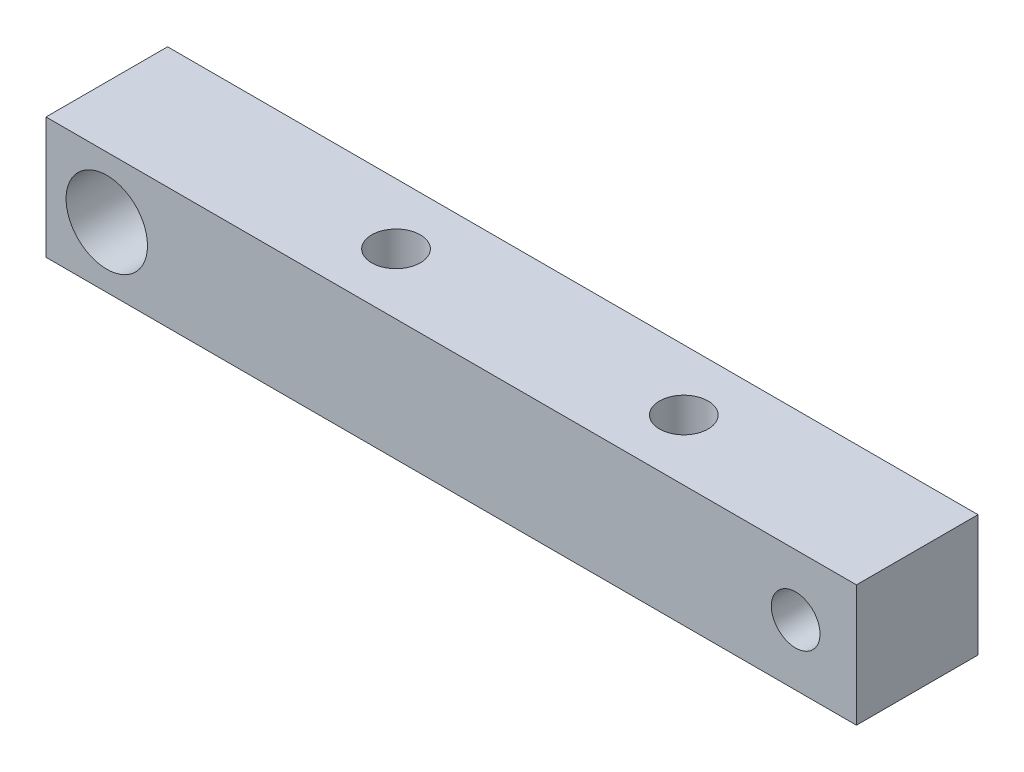
SolidWorks part; units mm, degrees
ref_plane "前基準面" through (0, 0, 0) normal (0, 0, 1) x (1, 0, 0)
ref_plane "上基準面" through (0, 0, 0) normal (0, 1, 0) x (1, 0, 0)
ref_plane "右基準面" through (0, 0, 0) normal (1, 0, 0) x (0, 0, -1)
sketch "草圖1" plane through (0, 0, 0) normal (0, 0, 1) x (1, 0, 0)
  line L1 (89.6066, 43.1835) -> (-10.3934, 43.1835)
  line L2 (89.6066, 43.1835) -> (89.6066, 28.1835)
  line L3 (89.6066, 28.1835) -> (-10.3934, 28.1835)
  line L4 (-10.3934, 43.1835) -> (-10.3934, 28.1835)
  circle A0 centre (82.1066, 35.6835) radius 3
  circle A1 centre (-2.8934, 35.6835) radius 5.0217
  dimension "D3" = 6
  dimension "D4" = 7.5
  dimension "D5" = 7.5
  dimension "D6" = 7.5
  dimension "D7" = 7.5
  dimension "D1" = 15
  dimension "D2" = 100
extrude "填料-伸長1" add sketch "草圖1" along normal blind 15
sketch "草圖2" plane through (0, 28.1835, 0) normal (0, -1, 0) x (1, 0, 0)
  line L0 (89.6066, 7.5) -> (-10.3934, 7.5) construction
  line L1 (89.6066, 15) -> (89.6066, 0) construction
  line L2 (-10.3934, 15) -> (-10.3934, 0) construction
  circle A0 centre (60.8068, 7.5) radius 3
  circle A1 centre (25.293, 7.5) radius 3
extrude "除料-伸長1" cut sketch "草圖2" against normal up to next
